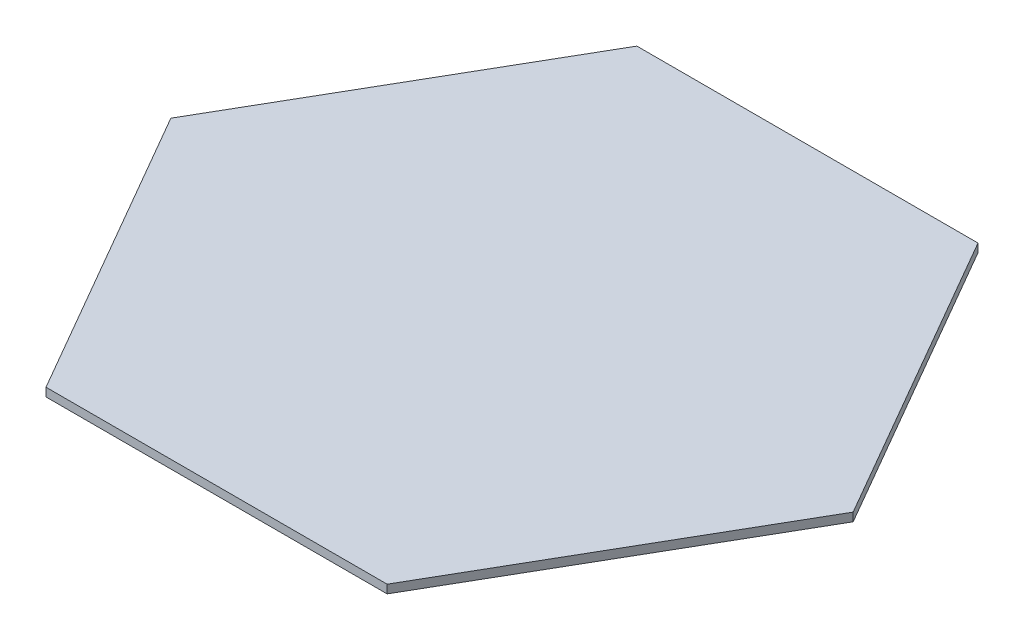
SolidWorks part; units mm, degrees
ref_plane "Front Plane" through (0, 0, 0) normal (0, 0, 1) x (1, 0, 0)
ref_plane "Top Plane" through (0, 0, 0) normal (0, 1, 0) x (1, 0, 0)
ref_plane "Right Plane" through (0, 0, 0) normal (1, 0, 0) x (0, 0, -1)
sketch "Sketch2" plane through (0, 0, 0) normal (0, 1, 0) x (1, 0, 0)
  line L1 (161.6581, 0) -> (80.829, 140)
  line L2 (80.829, 140) -> (-80.829, 140)
  line L3 (-80.829, 140) -> (-161.6581, 0)
  line L4 (-161.6581, 0) -> (-80.829, -140)
  line L5 (-80.829, -140) -> (80.829, -140)
  line L6 (80.829, -140) -> (161.6581, 0)
  circle A0 centre (0, 0) radius 140 construction
  dimension "D1" = 280
extrude "Boss-Extrude1" add sketch "Sketch2" along normal blind 4
